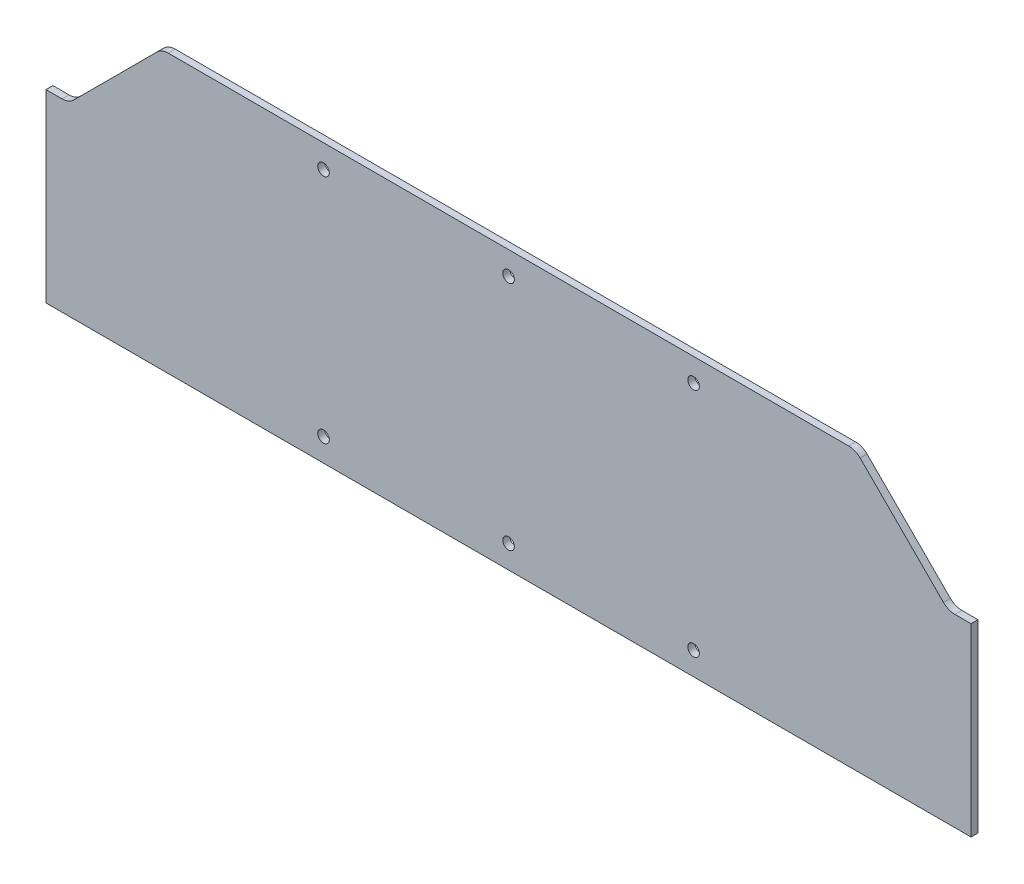
SolidWorks part; units mm, degrees
material "Acrylic (Medium-high impact)"
ref_plane "Front Plane" through (0, 0, 0) normal (0, 0, 1) x (1, 0, 0)
ref_plane "Top Plane" through (0, 0, 0) normal (0, 1, 0) x (1, 0, 0)
ref_plane "Right Plane" through (0, 0, 0) normal (1, 0, 0) x (0, 0, -1)
sketch "Sketch1" plane through (0, 0, 0) normal (0, 0, 1) x (1, 0, 0)
  line L1 (-200, -60) -> (200, -60)
  line L2 (-200, -60) -> (-200, 60)
  line L3 (-200, 60) -> (200, 60)
  line L4 (200, -60) -> (200, 60)
  line L5 (-200, -60) -> (200, 60) construction
  line L6 (-200, 60) -> (200, -60) construction
  point P0 (0, 0)
  dimension "D1" = 400
  dimension "D2" = 120
extrude "Boss-Extrude1" add sketch "Sketch1" along normal blind 3
sketch "Sketch2" plane through (0, 0, 0) normal (0, 0, -1) x (-1, 0, 0)
  line L0 (0, -1000) -> (0, 49000) construction
  line L1 (-200, 60) -> (200, 60) construction
  line L2 (200, 60) -> (147.1005, 60)
  line L3 (200, 60) -> (200, 19.8995)
  line L7 (152.0503, 57.9497) -> (188.0503, 21.9497)
  line L8 (200, 60) -> (200, -60) construction
  line L9 (-152.0503, 57.9497) -> (-188.0503, 21.9497)
  line L10 (-200, 60) -> (-200, 19.8995)
  line L11 (-200, 60) -> (-147.1005, 60)
  line L12 (-193, 19.8995) -> (-200, 19.8995)
  line L13 (-200, -60) -> (-200, 60) construction
  line L14 (193, 19.8995) -> (200, 19.8995)
  line L15 (200, 60) -> (200, -60) construction
  arc A2 (188.0503, 21.9497) -> (193, 19.8995) centre (193, 26.8995) ccw
  arc A3 (152.0503, 57.9497) -> (147.1005, 60) centre (147.1005, 53) ccw
  arc A4 (-152.0503, 57.9497) -> (-147.1005, 60) centre (-147.1005, 53) cw
  arc A5 (-188.0503, 21.9497) -> (-193, 19.8995) centre (-193, 26.8995) cw
  dimension "D3" = 7
  dimension "D7" = 7
  dimension "D1" = 7
  dimension "D2" = 33.1005
  dimension "D4" = 50.9117
  dimension "D5" = 7
  dimension "D6" = 147.1005
  dimension "D8" = 2.0503
extrude "Cut-Extrude1" cut sketch "Sketch2" against normal up to next
sketch "Sketch3" plane through (0, 0, 3) normal (0, 0, 1) x (1, 0, 0)
  line L2 (147.1005, 50) -> (-147.1005, 50)
  line L3 (147.1005, 50) -> (-147.1005, 50) construction
  line L4 (0, -1000) -> (0, 49000) construction
  line L5 (-200, -50) -> (200, -50)
  line L6 (-200, -50) -> (200, -50) construction
  circle A1 centre (-80, 50) radius 2.5
  circle A2 centre (0, 50) radius 2.5
  circle A4 centre (0, -50) radius 2.5
  circle A5 centre (-80, -50) radius 2.5
  circle A6 centre (80, -50) radius 2.5
  circle A7 centre (80, 50) radius 2.5
  dimension "D3" = 5
  dimension "D4" = 80
  dimension "D1" = 10
  dimension "D2" = 10
extrude "Cut-Extrude2" cut sketch "Sketch3" against normal up to next
